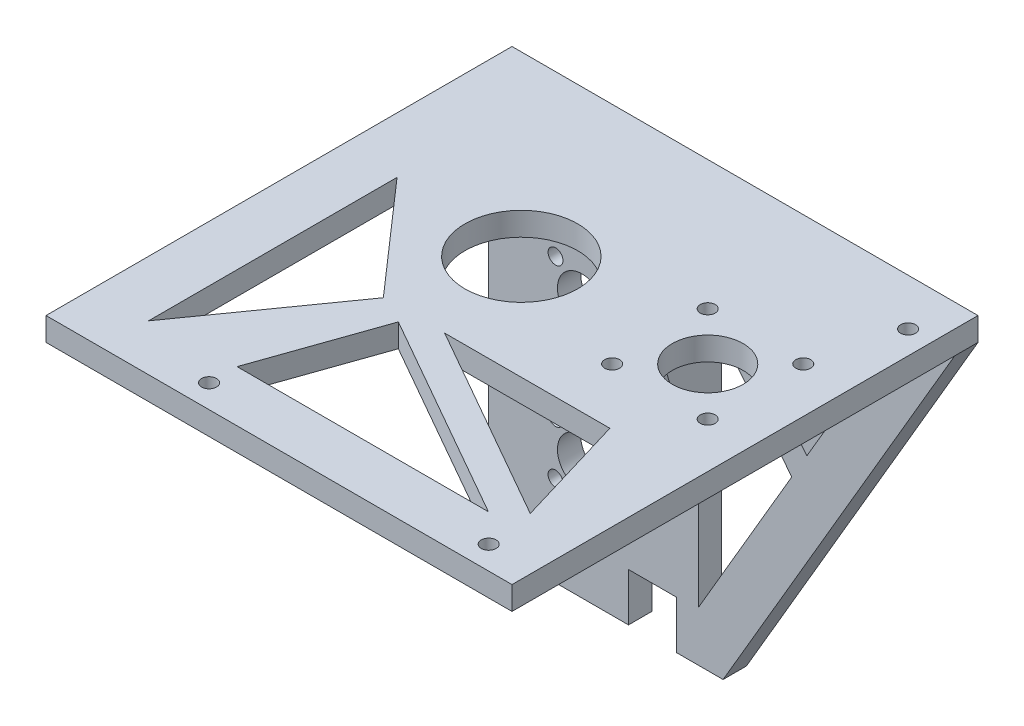
SolidWorks part; units mm, degrees
ref_plane "正面" through (0, 0, 0) normal (0, 0, 1) x (1, 0, 0)
ref_plane "平面" through (0, 0, 0) normal (0, 1, 0) x (1, 0, 0)
ref_plane "右側面" through (0, 0, 0) normal (1, 0, 0) x (0, 0, -1)
sketch "Sketch1" plane through (0, 0, 0) normal (0, 0, 1) x (1, 0, 0)
  line L1 (-40, 45) -> (40, 45)
  line L2 (-40, 45) -> (-40, -45)
  line L3 (-40, -45) -> (40, -45)
  line L4 (40, 45) -> (40, -45)
  line L5 (-40, 45) -> (40, -45) construction
  line L6 (-40, -45) -> (40, 45) construction
  point P0 (0, 0)
  dimension "D1" = 90
  dimension "D2" = 80
extrude "Boss-Extrude1" add sketch "Sketch1" along normal blind 5
sketch "Sketch2" plane through (0, 0, 5) normal (0, 0, 1) x (1, 0, 0)
  line L0 (-40, 10) -> (40, 10) construction
  line L1 (-40, 45) -> (-40, -45) construction
  line L2 (40, -45) -> (40, 45) construction
  line L3 (40, 45) -> (-40, 45) construction
  line L4 (0, 45) -> (0, -45) construction
  line L5 (-40, -45) -> (40, -45) construction
  line L7 (-25.6569, 15.6569) -> (-14.3431, 15.6569) construction
  line L8 (-25.6569, 15.6569) -> (-25.6569, 4.3431) construction
  line L9 (-25.6569, 4.3431) -> (-14.3431, 4.3431) construction
  line L10 (-14.3431, 15.6569) -> (-14.3431, 4.3431) construction
  line L11 (-25.6569, 15.6569) -> (-14.3431, 4.3431) construction
  line L12 (-25.6569, 4.3431) -> (-14.3431, 15.6569) construction
  circle A0 centre (-20, 10) radius 5.25
  circle A2 centre (-14.3431, 15.6569) radius 1.6
  circle A18 centre (-14.3431, 4.3431) radius 1.6
  circle A19 centre (-25.6569, 4.3431) radius 1.6
  circle A20 centre (-25.6569, 15.6569) radius 1.6
  circle A25 centre (-20, -20) radius 5.25
  circle A26 centre (-25.6569, -25.6569) radius 1.6
  circle A27 centre (-25.6569, -14.3431) radius 1.6
  circle A28 centre (-14.3431, -14.3431) radius 1.6
  circle A29 centre (-14.3431, -25.6569) radius 1.6
  point P30 (-20, 10)
  point P55 (-20, 10)
  dimension "D2" = 10.5
  dimension "D6" = 3.2
  dimension "D1" = 35
  dimension "D3" = 20
  dimension "D5" = 16
  dimension "D9" = 2
  dimension "D7" = 4
extrude "Cut-Extrude1" cut sketch "Sketch2" against normal up to next
sketch "Sketch3" plane through (0, 0, 5) normal (0, 0, 1) x (1, 0, 0)
  line L0 (40, -45) -> (40, 45) construction
  line L1 (-40, 45) -> (40, 45)
  line L2 (-40, 45) -> (-40, 40)
  line L3 (-40, 40) -> (40, 40)
  line L4 (40, 45) -> (40, 40)
  dimension "5" = 5
extrude "Boss-Extrude2" add sketch "Sketch3" along normal blind 95
sketch "Sketch4" plane through (0, 0, 5) normal (0, 0, 1) x (1, 0, 0)
  line L1 (-40, 40) -> (-29.7, 40)
  line L2 (-40, 40) -> (-40, 29.7)
  line L3 (-40, 29.7) -> (-29.7, 29.7)
  line L4 (-29.7, 40) -> (-29.7, 29.7)
  dimension "D1" = 10.3
  dimension "D2" = 10.3
extrude "Cut-Extrude2" cut sketch "Sketch4" against normal up to next
sketch "Sketch5" plane through (0, 45, 0) normal (0, 1, 0) x (1, 0, 0)
  line L0 (0, 0) -> (0, -100) construction
  line L1 (40, -100) -> (-40, -100) construction
  line L2 (40, 0) -> (-40, 0) construction
  line L3 (0, -38) -> (40, -38) construction
  circle A0 centre (0, -38) radius 12.1
  circle A2 centre (0, -38) radius 40 construction
  dimension "D2" = 24.2
  dimension "D4" = 90
  dimension "D5" = 80
  dimension "D1" = 38
extrude "Cut-Extrude3" cut sketch "Sketch5" against normal up to next
sketch "Sketch6" plane through (40, 0, 0) normal (1, 0, 0) x (0, 0, -1)
  line L4 (-100, 40) -> (-5, 40)
  line L5 (0, -45) -> (0, 45)
  line L7 (-100, 45) -> (-100, 40)
  line L8 (-100, 40) -> (-5, 40)
  line L11 (-100, 45) -> (-100, 40)
  line L12 (0, -45) -> (0, 45)
  line L18 (0, 45) -> (-100, 45)
  line L19 (0, 45) -> (-100, 45)
  line L20 (-5, 40) -> (-5, -45)
  line L21 (-5, 40) -> (-5, -45)
  line L22 (-5, -45) -> (0, -45)
  line L23 (-5, -45) -> (0, -45)
  dimension "D1" = 0
extrude "Boss-Extrude3" add sketch "Sketch6" along normal blind 20
sketch "Sketch7" plane through (0, 0, 5) normal (0, 0, 1) x (1, 0, 0)
  line L0 (-10, -45) -> (-10, 40) construction
  line L1 (-40, -45) -> (60, -45) construction
  line L2 (-29.7, 40) -> (60, 40) construction
  line L3 (-40, 29.7) -> (-40, -45) construction
  line L5 (-10, -45) -> (0.3, -45)
  line L6 (-10, -45) -> (-10, -34.7)
  line L7 (-10, -34.7) -> (0.3, -34.7)
  line L8 (0.3, -45) -> (0.3, -34.7)
  dimension "D1" = 30
  dimension "D2" = 10.3
  dimension "D3" = 10.3
extrude "Cut-Extrude4" cut sketch "Sketch7" against normal up to next
sketch "Sketch8" plane through (0, 45, 0) normal (0, 1, 0) x (1, 0, 0)
  line L0 (0, -38) -> (60, -38) construction
  line L1 (60, 0) -> (60, -100) construction
  circle A0 centre (40, -38) radius 7.6
  dimension "D2" = 15.2
  dimension "D1" = 40
extrude "Cut-Extrude5" cut sketch "Sketch8" against normal blind 10
sketch "Sketch9" plane through (0, 40, 0) normal (0, -1, 0) x (1, 0, 0)
  line L0 (-40, 95) -> (60, 95) construction
  line L1 (-40, 100) -> (-40, 0) construction
  line L2 (60, 100) -> (60, 5) construction
  line L3 (-40, 100) -> (60, 100) construction
  circle A0 centre (50, 95) radius 1.6
  circle A1 centre (-10, 95) radius 1.6
  dimension "D3" = 3.2
  dimension "D4" = 3.2
  dimension "D1" = 5
  dimension "D2" = 10
  dimension "D5" = 30
extrude "Cut-Extrude6" cut sketch "Sketch9" against normal up to next
sketch "Sketch10" plane through (0, 40, 0) normal (0, -1, 0) x (1, 0, 0)
  line L0 (-40, 10) -> (60, 10) construction
  line L1 (-40, 100) -> (-40, 0) construction
  line L2 (60, 100) -> (60, 5) construction
  line L3 (-29.7, 5) -> (60, 5) construction
  circle A0 centre (55, 10) radius 1.6
  dimension "D2" = 3.2
  dimension "D1" = 5
  dimension "D3" = 5
extrude "Cut-Extrude7" cut sketch "Sketch10" against normal blind 35
sketch "Sketch11" plane through (0, 40, 0) normal (0, -1, 0) x (1, 0, 0)
  line L0 (40, 38) -> (60, 38) construction
  line L1 (60, 100) -> (60, 5) construction
  line L2 (40, 38) -> (60, 58) construction
  line L3 (40, 38) -> (50.253, 48.253) construction
  circle A0 centre (50.253, 48.253) radius 1.6
  circle A1 centre (29.747, 48.253) radius 1.6
  circle A2 centre (29.747, 27.747) radius 1.6
  circle A3 centre (50.253, 27.747) radius 1.6
  dimension "D2" = 3.2
  dimension "D1" = 45
  dimension "D3" = 14.5
  dimension "D5" = 14.5
  dimension "D4" = 4
extrude "Cut-Extrude8" cut sketch "Sketch11" against normal blind 35
sketch "Sketch12" plane through (0, 0, 5) normal (0, 0, 1) x (1, 0, 0)
  line L0 (60, 40) -> (10.3, -45)
  line L1 (0.3, -45) -> (60, -45) construction
  line L2 (0.3, -45) -> (0.3, -34.7) construction
  line L3 (10.3, -45) -> (60, -45)
  line L4 (60, -45) -> (60, 40)
  dimension "D1" = 10
extrude "Cut-Extrude10" cut sketch "Sketch12" against normal up to next
sketch "Sketch13" plane through (0, 0, 5) normal (0, 0, 1) x (1, 0, 0)
  line L0 (5, 30) -> (42.569, 30) construction
  line L1 (42.569, 30) -> (5, -34.2528) construction
  line L2 (5, -34.2528) -> (5, 30) construction
  line L3 (60, 40) -> (10.3, -45) construction
  line L5 (-29.7, 40) -> (60, 40) construction
  line L6 (-40, 29.7) -> (-40, -45) construction
  line L7 (-10, -34.7) -> (-10, -45) construction
  line L8 (-40, 40) -> (60, 40) construction
  line L9 (5, 30) -> (26.6618, 2.7946) construction
  line L10 (5, 25.1838) -> (25.0381, 0.0176)
  line L11 (8.8348, 30) -> (28.2855, 5.5715)
  line L12 (8.8348, 30) -> (42.569, 30)
  line L13 (42.569, 30) -> (28.2855, 5.5715)
  line L14 (5, 25.1838) -> (5, -34.2528)
  line L15 (5, -34.2528) -> (25.0381, 0.0176)
  point P16 (15.8309, 16.3973)
  dimension "D1" = 15
  dimension "D2" = 10
  dimension "D3" = 10
  dimension "D4" = 3
  dimension "D5" = 3
extrude "Cut-Extrude11" cut sketch "Sketch13" against normal up to next
sketch "Sketch15" plane through (0, 40, 0) normal (0, -1, 0) x (1, 0, 0)
  line L0 (-40, 100) -> (-40, 0) construction
  line L1 (-40, 100) -> (-30, 100) construction
  line L2 (-40, 100) -> (-40, 5) construction
  line L3 (-40, 5) -> (-30, 5) construction
  line L4 (-30, 100) -> (-30, 5) construction
  line L5 (-40, 5) -> (-10, 5) construction
  line L6 (0, 60.5) -> (41.4601, 60.4526)
  line L7 (60, 100) -> (-20, 100) construction
  line L8 (60, 100) -> (60, 90) construction
  line L9 (60, 90) -> (-20, 90) construction
  line L10 (-20, 100) -> (-20, 90) construction
  line L11 (41.4601, 60.4526) -> (50, 89)
  line L12 (50, 89) -> (-10, 89)
  line L13 (-10, 89) -> (0, 60.5)
  line L14 (60, 100) -> (60, 5) construction
  line L15 (-28.0106, 90) -> (-28.0106, 36.6534)
  line L16 (-28.0106, 36.6534) -> (-7.1091, 60.5)
  line L17 (-7.1091, 60.5) -> (-28.0106, 90)
  circle A0 centre (40, 38) radius 22.5 construction
  circle A1 centre (0, 38) radius 22.5 construction
  circle A2 centre (0, 38) radius 12.1 construction
  dimension "D2" = 45
  dimension "D4" = 45
  dimension "D1" = 10
  dimension "D3" = 80
  dimension "10" = 10
  dimension "D5" = 10
  dimension "D6" = 1
  dimension "D7" = 10
extrude "Cut-Extrude12" cut sketch "Sketch15" against normal up to next
sketch "Sketch16" plane through (0, 45, 0) normal (0, 1, 0) x (1, 0, 0)
  line L0 (0, -60.5) -> (50, -89) construction
  line L1 (41.4601, -60.4526) -> (-10, -89) construction
  line L2 (-7.1091, -60.5) -> (-28.0106, -60.5) construction
  line L3 (-28.0106, -36.6534) -> (-28.0106, -90) construction
  line L4 (-1.0097, -63.3776) -> (43.9419, -89)
  line L5 (0, -60.5) -> (-10, -89) construction
  line L6 (-10, -89) -> (50, -89) construction
  line L7 (6.046, -60.4931) -> (48.7547, -84.837)
  line L8 (41.4601, -60.4526) -> (0, -60.5) construction
  line L9 (50, -89) -> (41.4601, -60.4526) construction
  line L10 (-1.0097, -63.3776) -> (0, -60.5)
  line L11 (0, -60.5) -> (6.046, -60.4931)
  line L12 (48.7547, -84.837) -> (50, -89)
  line L13 (50, -89) -> (43.9419, -89)
  dimension "D1" = 3
  dimension "D2" = 3
extrude "Boss-Extrude4" add sketch "Sketch16" against normal up to surface (5 mm away) up to face at (-21.0434, 40, 62.3845)
ref_plane "Plane1" through (60, 40, 5) normal (1, 0, 0) x (0, 0, -1)
sketch "Sketch20" plane through (5, 0, 0) normal (1, 0, 0) x (0, 0, -1)
  line L0 (-20, 40) -> (-5, -10)
  line L1 (-100, 40) -> (-5, 40) construction
  line L2 (-5, 40) -> (-5, -45) construction
  line L3 (-5, -10) -> (-5, 40)
  line L4 (-5, 40) -> (-20, 40)
  dimension "D1" = 15
  dimension "D2" = 50
extrude "Boss-Extrude5" add sketch "Sketch20" against normal blind 4
